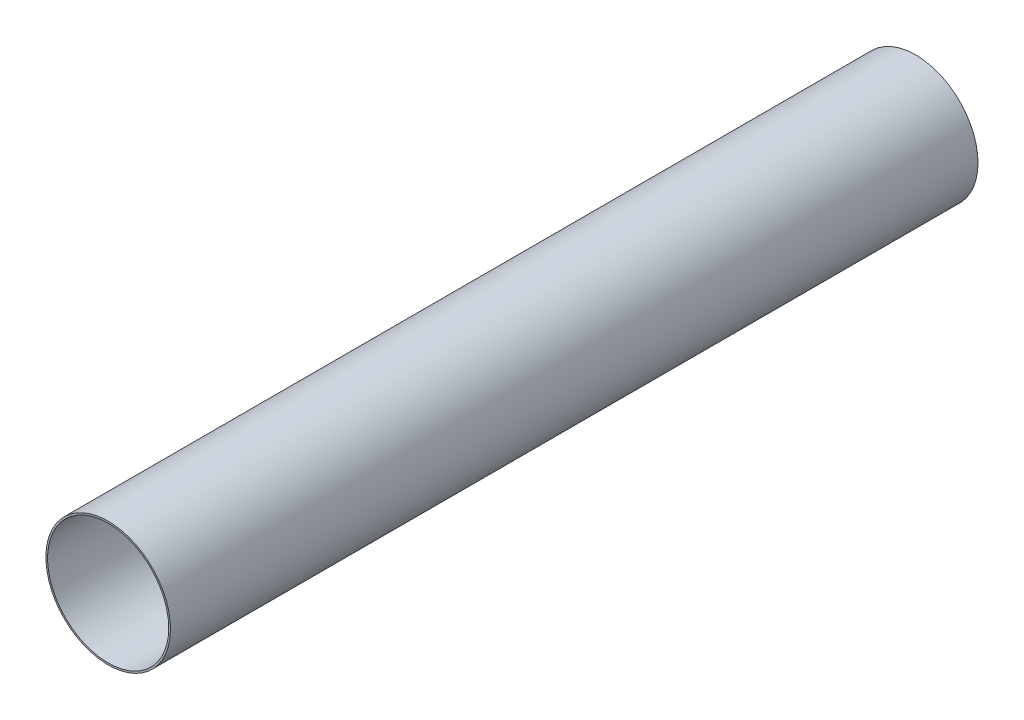
SolidWorks part; units mm, degrees
ref_plane "Plan de face" through (0, 0, 0) normal (0, 0, 1) x (1, 0, 0)
ref_plane "Plan de dessus" through (0, 0, 0) normal (0, 1, 0) x (1, 0, 0)
ref_plane "Plan de droite" through (0, 0, 0) normal (1, 0, 0) x (0, 0, -1)
sketch "Esquisse2" plane through (0, 0, 0) normal (0, 0, 1) x (1, 0, 0)
  circle A0 centre (0, 0) radius 78.359
  circle A1 centre (0, 0) radius 76.2
  dimension "D1" = 156.718
  dimension "D2" = 152.4
extrude "Boss.-Extru.1" add sketch "Esquisse2" along normal blind 1016
